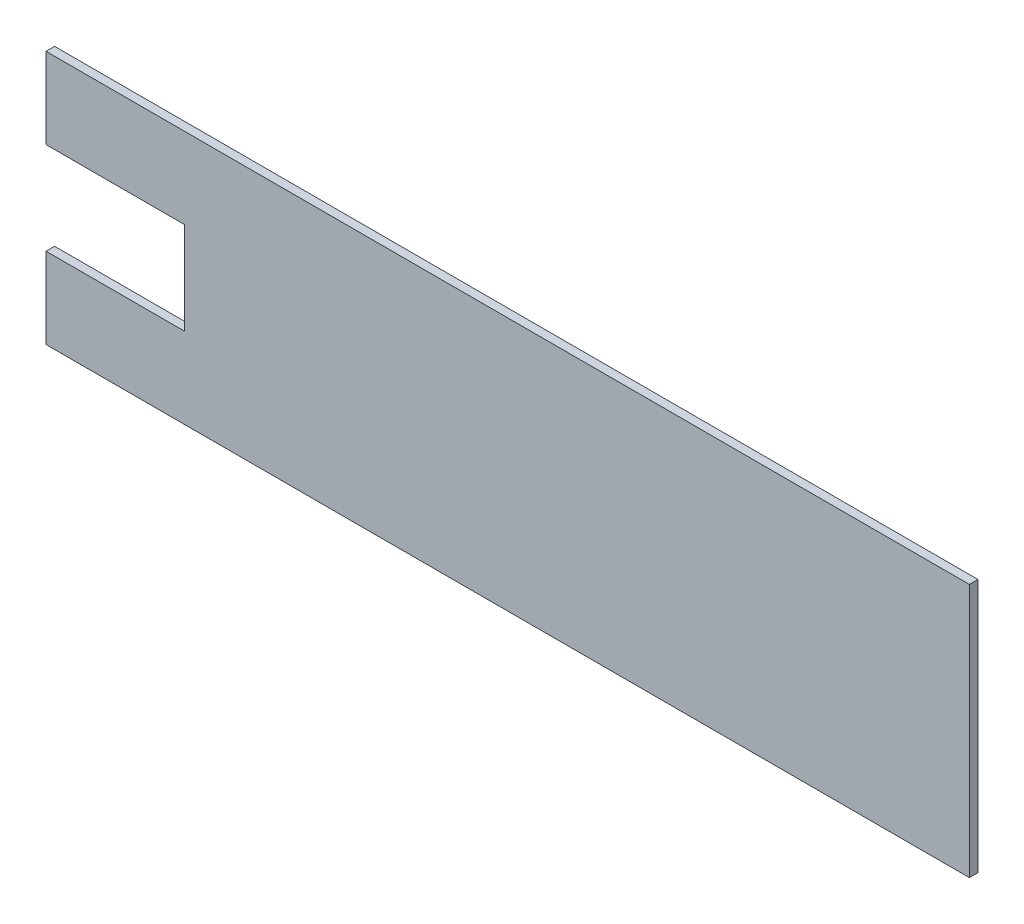
SolidWorks part; units mm, degrees
ref_plane "Front Plane" through (0, 0, 0) normal (0, 0, 1) x (1, 0, 0)
ref_plane "Top Plane" through (0, 0, 0) normal (0, 1, 0) x (1, 0, 0)
ref_plane "Right Plane" through (0, 0, 0) normal (1, 0, 0) x (0, 0, -1)
sketch "Sketch1" plane through (0, 0, 0) normal (0, 0, 1) x (1, 0, 0)
  line L1 (0, 0) -> (254, 0)
  line L2 (0, 0) -> (0, 69.85)
  line L3 (0, 69.85) -> (254, 69.85)
  line L4 (254, 0) -> (254, 69.85)
  dimension "D1" = 69.85
  dimension "D2" = 254
extrude "Boss-Extrude1" add sketch "Sketch1" along normal blind 2.3622
sketch "Sketch2" plane through (0, 0, 2.3622) normal (0, 0, 1) x (1, 0, 0)
  line L0 (0, 69.85) -> (0, 0) construction
  line L1 (0, 47.625) -> (38.1, 47.625)
  line L2 (0, 47.625) -> (0, 22.225)
  line L3 (0, 22.225) -> (38.1, 22.225)
  line L4 (38.1, 47.625) -> (38.1, 22.225)
  line L5 (254, 0) -> (254, 69.85) construction
  point P6 (38.1, 34.925)
  point P7 (254, 34.925)
  dimension "D1" = 25.4
  dimension "D2" = 38.1
extrude "Cut-Extrude1" cut sketch "Sketch2" against normal through all
